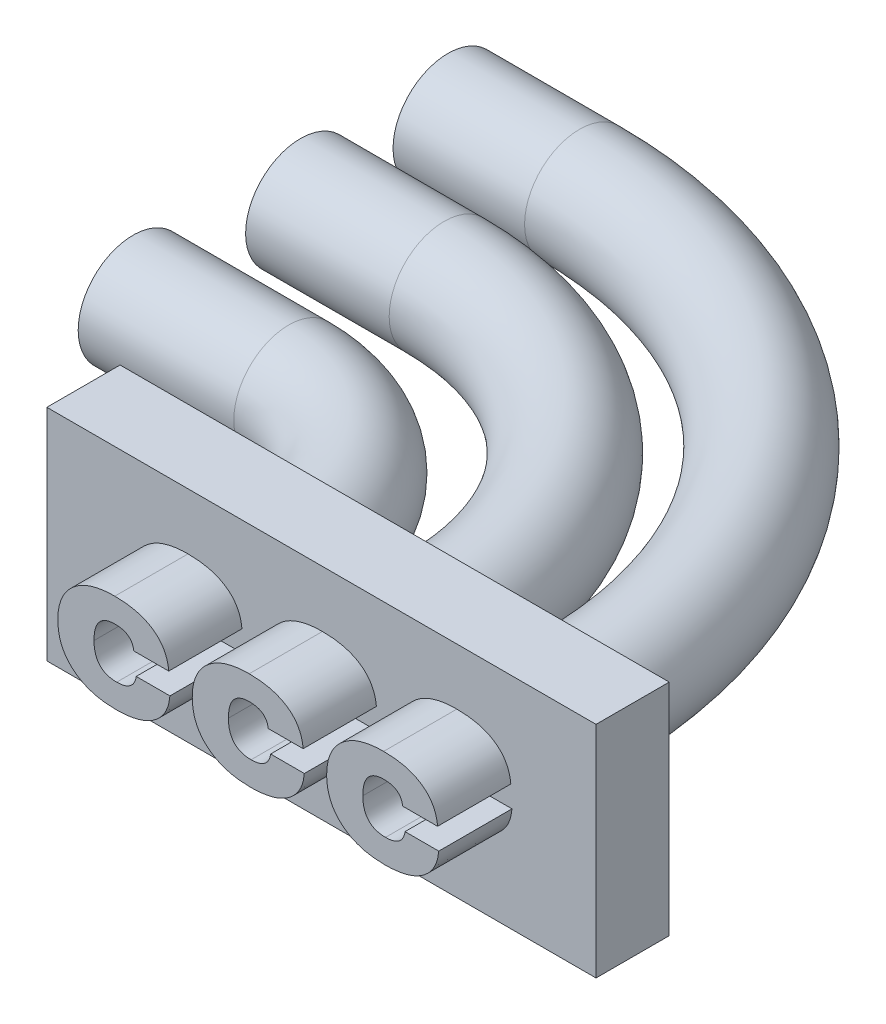
SolidWorks part; units mm, degrees
ref_plane "Front Plane" through (0, 0, 0) normal (0, 0, 1) x (1, 0, 0)
ref_plane "Top Plane" through (0, 0, 0) normal (0, 1, 0) x (1, 0, 0)
ref_plane "Right Plane" through (0, 0, 0) normal (1, 0, 0) x (0, 0, -1)
sketch "Sketch1" plane through (0, 0, 0) normal (0, 0, 1) x (1, 0, 0)
  line L1 (-7.5, 3) -> (7.5, 3)
  line L2 (-7.5, 3) -> (-7.5, -3)
  line L3 (-7.5, -3) -> (7.5, -3)
  line L4 (7.5, 3) -> (7.5, -3)
  line L5 (-7.5, 3) -> (7.5, -3) construction
  line L6 (-7.5, -3) -> (7.5, 3) construction
  point P0 (0, 0)
  dimension "D1" = 15
  dimension "D2" = 6
extrude "Boss-Extrude1" add sketch "Sketch1" along normal blind 2
sketch "Sketch2" plane through (0, 0, 2) normal (0, 0, 1) x (1, 0, 0)
  text T0 "CCC" font "Swis721 Blk BT" height in points 10
extrude "Boss-Extrude2" add sketch "Sketch2" along normal blind 2
sketch "Sketch3" plane through (0, 0, 0) normal (0, 1, 0) x (1, 0, 0)
  line L0 (7.5, 0) -> (-7.5, 0) construction
  line L1 (2.9487, 0) -> (4.4487, 0)
  line L2 (2.9487, 0) -> (2.9487, 12.6)
  line L3 (-3.644, -2) -> (-3.644, 5.3789) construction
  line L4 (4.4487, 0) -> (4.4487, 14.1)
  line L5 (-4.394, 0) -> (-2.894, 0)
  line L6 (-4.394, 0) -> (-4.394, 4)
  line L7 (0.0274, -2) -> (0.0274, 4.6797) construction
  line L8 (-2.894, 0) -> (-2.894, 4)
  line L9 (-2.894, 4) -> (-4.394, 4)
  line L10 (-0.7226, 0) -> (0.7774, 0)
  line L13 (-0.7226, 0) -> (-0.7226, 8.6)
  line L14 (3.6987, -2) -> (3.6987, 2.787) construction
  line L15 (0.7774, 0) -> (0.7774, 10.1)
  line L16 (0.7774, 10.1) -> (-2.4226, 10.1)
  line L17 (-2.4226, 14.1) -> (4.4487, 14.1)
  line L18 (-0.7226, 8.6) -> (-2.4226, 8.6)
  line L19 (-2.4226, 10.1) -> (-2.4226, 8.6)
  line L20 (-2.4226, 14.1) -> (-2.4226, 12.6)
  line L21 (-2.4226, 12.6) -> (2.9487, 12.6)
  dimension "D1" = 1.5
  dimension "D2" = 4
  dimension "D3" = 1.5
  dimension "D4" = 1.5
  dimension "D5" = 4.6
  dimension "D6" = 1.5
  dimension "D7" = 2.5
  dimension "D8" = 1.5
  dimension "D9" = 1.7
extrude "Boss-Extrude3" add sketch "Sketch3" along normal mid plane 4
sketch "Sketch4" [suppressed] plane through (0, 2, 0) normal (0, 1, 0) x (1, 0, 0)
  line L1 (-2.4226, 10.1) -> (-2.4226, 8.6) construction
  line L2 (-2.894, 4) -> (-11.894, 4)
  line L3 (-2.894, 4) -> (-2.894, 5.5)
  line L4 (-2.894, 5.5) -> (-11.894, 5.5)
  line L5 (-11.894, 4) -> (-11.894, 5.5)
  dimension "D1" = 9
extrude "Boss-Extrude4" [suppressed] add sketch "Sketch4" against normal up to surface (4 mm away)
sketch "Sketch5" [suppressed] plane through (-2.4226, 0, 0) normal (-1, 0, 0) x (0, 0, 1)
  line L4 (-10.1, -2) -> (-8.6, -2)
  line L5 (-8.6, -2) -> (-8.6, 2)
  line L6 (-8.6, 2) -> (-10.1, 2)
  line L7 (-10.1, 2) -> (-10.1, -2)
  line L8 (-10.1, -2) -> (-8.6, -2)
  line L9 (-8.6, -2) -> (-8.6, 2)
  line L10 (-8.6, 2) -> (-10.1, 2)
  line L11 (-10.1, 2) -> (-10.1, -2)
  line L12 (-14.1, -2) -> (-12.6, -2)
  line L13 (-12.6, -2) -> (-12.6, 2)
  line L14 (-12.6, 2) -> (-14.1, 2)
  line L15 (-14.1, 2) -> (-14.1, -2)
  line L16 (-14.1, -2) -> (-12.6, -2)
  line L17 (-12.6, -2) -> (-12.6, 2)
  line L18 (-12.6, 2) -> (-14.1, 2)
  line L19 (-14.1, 2) -> (-14.1, -2)
  dimension "D1" = 0
  dimension "D2" = 0
extrude "Boss-Extrude5" [suppressed] add sketch "Sketch5" along normal up to surface (9.4714 mm away)
sketch "Sketch6" plane through (0, 0, 0) normal (0, 0, -1) x (-1, 0, 0)
  line L0 (-4.4487, 0) -> (-2.9487, 0) construction
  line L1 (-4.4487, 2) -> (-4.4487, -2) construction
  line L2 (-2.9487, 2) -> (-2.9487, -2) construction
  line L3 (-0.7774, 0) -> (0.7226, 0) construction
  line L4 (-0.7774, 2) -> (-0.7774, -2) construction
  line L5 (0.7226, 2) -> (0.7226, -2) construction
  line L6 (2.894, 0) -> (4.394, 0) construction
  line L7 (2.894, 2) -> (2.894, -2) construction
  line L8 (4.394, 2) -> (4.394, -2) construction
  circle A0 centre (-3.6987, 0) radius 1.5
  dimension "D1" = 3
sketch "Sketch7" plane through (0, 0, 0) normal (0, 0, -1) x (-1, 0, 0)
  circle A0 centre (0, 0) radius 1.5
  dimension "D1" = 3
sketch "Sketch8" plane through (0, 0, 0) normal (0, 0, -1) x (-1, 0, 0)
  line L0 (2.894, 0) -> (4.394, 0) construction
  circle A0 centre (3.644, 0) radius 1.5
  dimension "D1" = 3
sketch "Sketch9" plane through (0, 0, 0) normal (0, 1, 0) x (1, 0, 0)
  line L0 (-3.644, 0) -> (-3.644, 0.75)
  line L1 (-2.894, 0) -> (-4.394, 0) construction
  line L2 (-7.644, 4.75) -> (-11.894, 4.75)
  arc A0 (-3.644, 0.75) -> (-7.644, 4.75) centre (-7.644, 0.75) ccw
  point P7 (-3.644, 4.75)
  dimension "D3" = 4
  dimension "D1" = 4.75
  dimension "D2" = 8.25
sketch "Sketch10" plane through (0, 0, 0) normal (0, 1, 0) x (1, 0, 0)
  line L0 (0.0274, 0) -> (0.0274, 1.35)
  line L1 (0.7774, 0) -> (-0.7226, 0) construction
  line L2 (-7.9726, 9.35) -> (-11.894, 9.35)
  arc A0 (0.0274, 1.35) -> (-7.9726, 9.35) centre (-7.9726, 1.35) ccw
  point P7 (0.0274, 9.35)
  dimension "D3" = 8
  dimension "D1" = 11.9214
  dimension "D2" = 9.35
sketch "Sketch11" plane through (0, 0, 0) normal (0, 1, 0) x (1, 0, 0)
  line L0 (3.6987, 0) -> (3.6987, 1.35)
  line L1 (4.4487, 0) -> (2.9487, 0) construction
  line L2 (-8.3013, 13.35) -> (-11.894, 13.35)
  arc A0 (3.6987, 1.35) -> (-8.3013, 13.35) centre (-8.3013, 1.35) ccw
  point P7 (3.6987, 13.35)
  dimension "D3" = 12
  dimension "D1" = 13.35
  dimension "D2" = 15.5928
sketch "Sketch12" plane through (7.5, 0, 0) normal (1, 0, 0) x (0, 0, -1)
  line L1 (0, -3) -> (14.1, -3)
  line L2 (0, -3) -> (0, 2)
  line L3 (0, 2) -> (14.1, 2)
  line L4 (14.1, -3) -> (14.1, 2)
extrude "Cut-Extrude1" cut sketch "Sketch12" against normal through all
sweep "Sweep1" add profiles "Sketch8" path "Sketch9"
sweep "Sweep2" add profiles "Sketch7" path "Sketch10"
sweep "Sweep3" add profiles "Sketch6" path "Sketch11"
